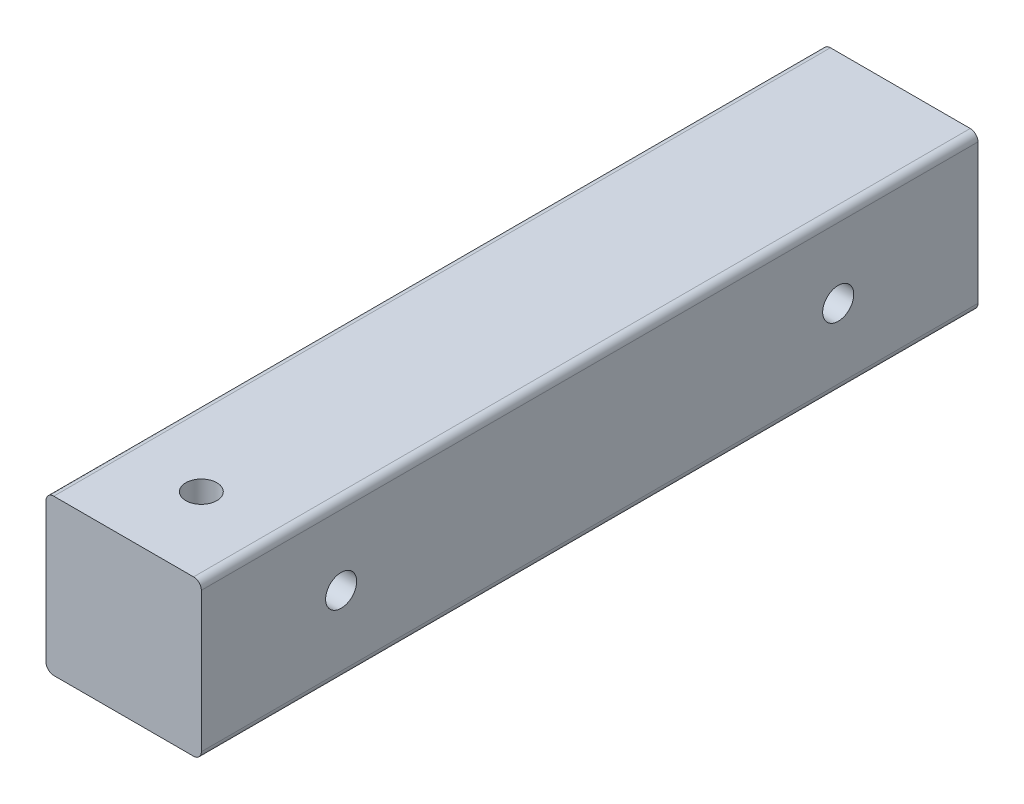
SolidWorks part; units mm, degrees
ref_plane "前视基准面" through (0, 0, 0) normal (0, 0, 1) x (1, 0, 0)
ref_plane "上视基准面" through (0, 0, 0) normal (0, 1, 0) x (1, 0, 0)
ref_plane "右视基准面" through (0, 0, 0) normal (1, 0, 0) x (0, 0, -1)
sketch "草图1" plane through (0, 0, 0) normal (0, 0, 1) x (1, 0, 0)
  line L1 (0, 0) -> (20, 0)
  line L2 (0, 0) -> (0, 20)
  line L3 (0, 20) -> (20, 20)
  line L4 (20, 0) -> (20, 20)
  dimension "D1" = 20
  dimension "D2" = 20
extrude "凸台-拉伸1" add sketch "草图1" along normal blind 100
sketch "草图2" plane through (20, 0, 0) normal (1, 0, 0) x (0, 0, -1)
  line L0 (0, 0) -> (0, 20) construction
  line L1 (-100, 0) -> (-100, 20) construction
  circle A0 centre (-18, 10) radius 2
  circle A1 centre (-82, 10) radius 2
  point P8 (-100, 10)
  point P9 (0, 0)
  dimension "D2" = 4
  dimension "D1" = 18
  dimension "D3" = 18
extrude "切除-拉伸1" cut sketch "草图2" against normal blind 20
sketch "草图3" plane through (0, 0, 0) normal (0, -1, 0) x (1, 0, 0)
  line L0 (0, 100) -> (20, 100) construction
  circle A0 centre (10, 90) radius 2
  point P4 (10, 100)
  dimension "D2" = 4
  dimension "D1" = 10
extrude "切除-拉伸2" cut sketch "草图3" against normal blind 20
fillet "圆角1" radius 1 4 edges at (0, 20, 50) (20, 20, 50) (20, 0, 50) (0, 0, 50)
